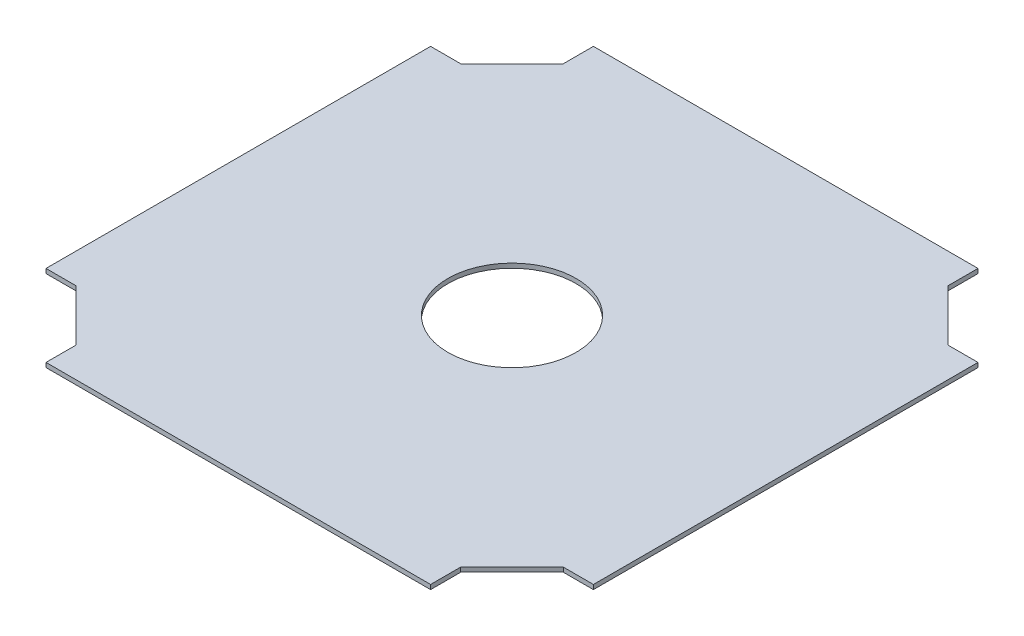
SolidWorks part; units mm, degrees
ref_plane "Front Plane" through (0, 0, 0) normal (0, 0, 1) x (1, 0, 0)
ref_plane "Top Plane" through (0, 0, 0) normal (0, 1, 0) x (1, 0, 0)
ref_plane "Right Plane" through (0, 0, 0) normal (1, 0, 0) x (0, 0, -1)
sketch "Sketch1" plane through (0, 0, 0) normal (0, 1, 0) x (1, 0, 0)
  line L0 (-363.5, 423.5) -> (-363.5, 403.5)
  line L1 (0, 0) -> (-427, 0) construction
  line L2 (0, 63.5) -> (0, 363.5)
  line L3 (-63.5, 427) -> (-363.5, 427)
  line L4 (-427, 63.5) -> (-427, 363.5)
  line L5 (-363.5, 403.5) -> (-403.5, 363.5)
  line L6 (-403.5, 363.5) -> (-423.5, 363.5)
  line L7 (-423.5, 363.5) -> (-427, 363.5)
  line L8 (-363.5, 423.5) -> (-363.5, 427)
  line L9 (-427, 427) -> (-427, 363.5) construction
  line L10 (-427, 427) -> (-363.5, 427) construction
  line L11 (-213.5, 0) -> (-213.5, 427) construction
  line L12 (-63.5, 423.5) -> (-63.5, 427)
  line L13 (-3.5, 363.5) -> (0, 363.5)
  line L14 (-63.5, 423.5) -> (-63.5, 403.5)
  line L15 (-63.5, 403.5) -> (-23.5, 363.5)
  line L16 (-23.5, 363.5) -> (-3.5, 363.5)
  line L17 (-213.5, 213.5) -> (-427, 213.5) construction
  line L18 (-3.5, 63.5) -> (0, 63.5)
  line L19 (-23.5, 63.5) -> (-3.5, 63.5)
  line L20 (-63.5, 23.5) -> (-23.5, 63.5)
  line L21 (-63.5, 3.5) -> (-63.5, 23.5)
  line L22 (-63.5, 3.5) -> (-63.5, 0)
  line L23 (-403.5, 63.5) -> (-423.5, 63.5)
  line L24 (-423.5, 63.5) -> (-427, 63.5)
  line L25 (-363.5, 23.5) -> (-403.5, 63.5)
  line L26 (-363.5, 3.5) -> (-363.5, 23.5)
  line L27 (-363.5, 3.5) -> (-363.5, 0)
  line L28 (-63.5, 427) -> (0, 427) construction
  line L29 (0, 363.5) -> (0, 427) construction
  line L30 (0, 63.5) -> (0, 0) construction
  line L31 (-363.5, 0) -> (-63.5, 0)
  line L32 (-427, 63.5) -> (-427, 0) construction
  dimension "D1" = 427
  dimension "D2" = 427
  dimension "D3" = 363.5
  dimension "D4" = 3.5
  dimension "D5" = 363.5
  dimension "D6" = 3.5
  dimension "D7" = 23.5
  dimension "D8" = 56.5685
extrude "Boss-Extrude1" add sketch "Sketch1" along normal blind 3.5
sketch "Sketch2" plane through (0, 3.5, 0) normal (0, 1, 0) x (1, 0, 0)
  line L0 (-213.5, 0) -> (-213.5, 427) construction
  line L2 (-63.5, 427) -> (-363.5, 427) construction
  line L3 (0, 213.5) -> (-427, 213.5) construction
  line L4 (0, 63.5) -> (0, 363.5) construction
  line L5 (-427, 363.5) -> (-427, 63.5) construction
  line L6 (-363.5, 0) -> (-63.5, 0) construction
  circle A0 centre (-213.5, 213.5) radius 50
  point P2 (-213.5, 4.1164)
  point P3 (-213.5, 1.1201)
  point P14 (-213.5, 0)
  dimension "D1" = 100
extrude "Cut-Extrude1" cut sketch "Sketch2" against normal blind 10
